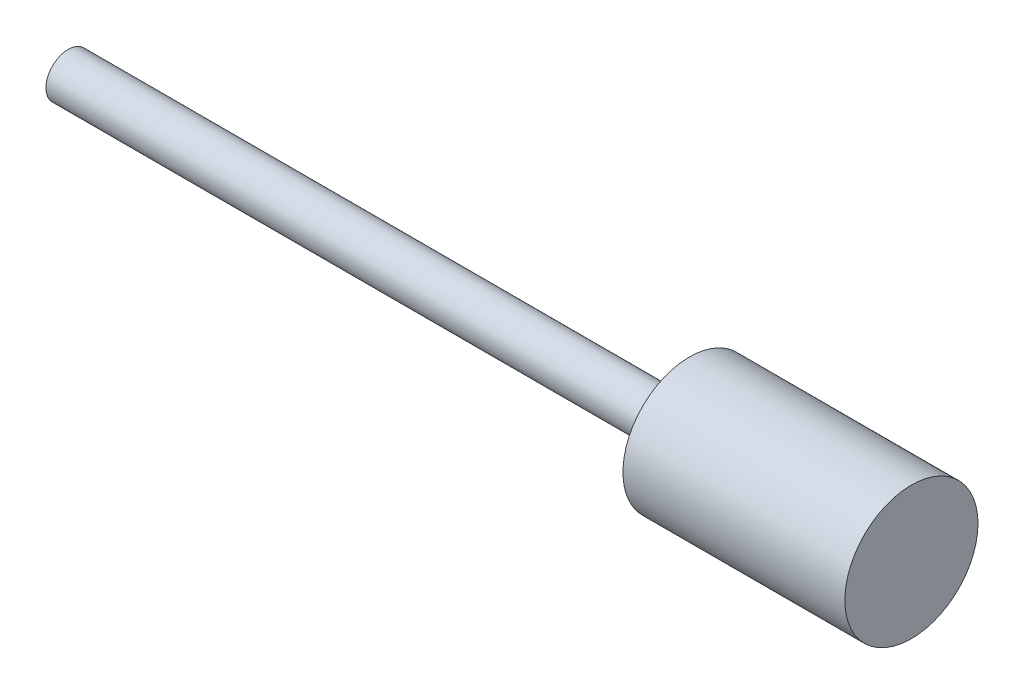
SolidWorks part; units mm, degrees
ref_plane "Front Plane" through (0, 0, 0) normal (0, 0, 1) x (1, 0, 0)
ref_plane "Top Plane" through (0, 0, 0) normal (0, 1, 0) x (1, 0, 0)
ref_plane "Right Plane" through (0, 0, 0) normal (1, 0, 0) x (0, 0, -1)
sketch "Sketch1" plane through (0, 0, 0) normal (1, 0, 0) x (0, 0, -1)
  circle A0 centre (0, 0) radius 5
  dimension "D1" = 10
extrude "Boss-Extrude1" add sketch "Sketch1" along normal blind 140
sketch "Sketch2" plane through (140, 0, 0) normal (1, 0, 0) x (0, 0, -1)
  circle A0 centre (0, 0) radius 15
  dimension "D1" = 30
extrude "Boss-Extrude2" add sketch "Sketch2" along normal blind 50
